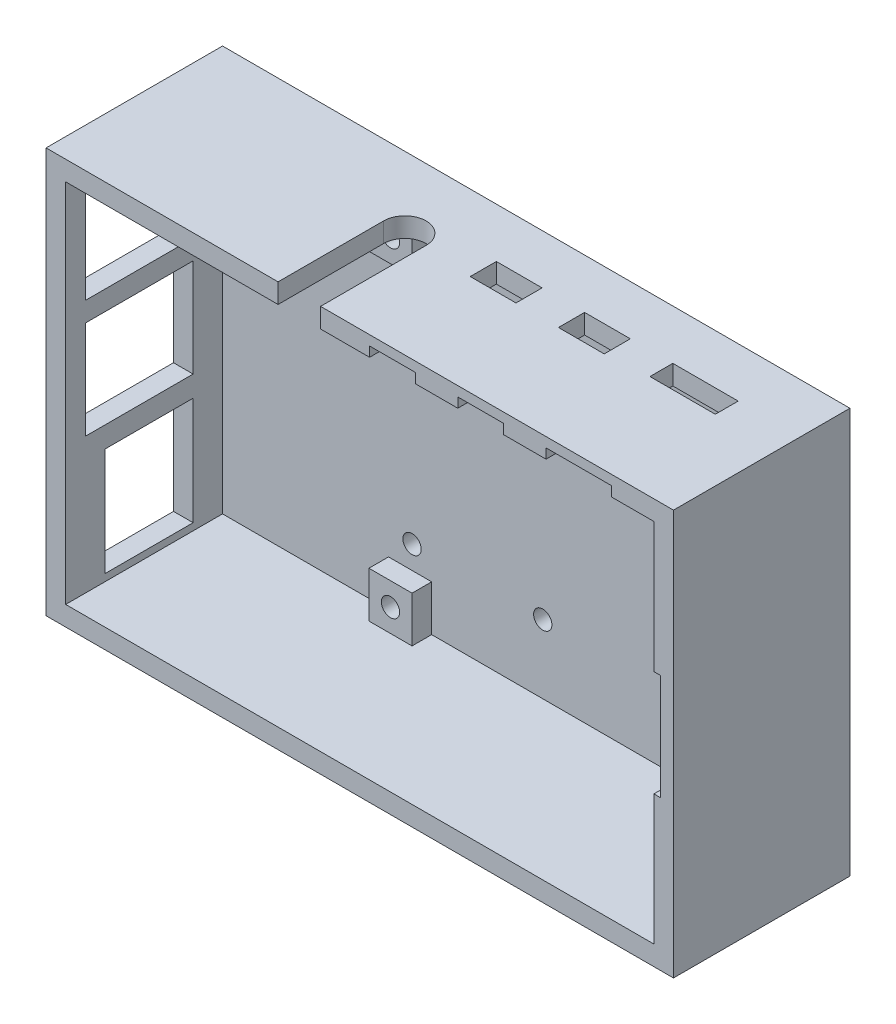
SolidWorks part; units mm, degrees
ref_plane "정면" through (0, 0, 0) normal (0, 0, 1) x (1, 0, 0)
ref_plane "윗면" through (0, 0, 0) normal (0, 1, 0) x (1, 0, 0)
ref_plane "우측면" through (0, 0, 0) normal (1, 0, 0) x (0, 0, -1)
sketch "스케치1" plane through (0, 0, 0) normal (0, 0, 1) x (1, 0, 0)
  line L0 (-16.3, 24.5) -> (41.7, 24.5) construction
  line L1 (-45, 28) -> (45, 28)
  line L2 (-45, 28) -> (-45, -28)
  line L3 (-45, -28) -> (45, -28)
  line L4 (45, 28) -> (45, -28)
  line L5 (-45, 28) -> (45, -28) construction
  line L6 (-45, -28) -> (45, 28) construction
  line L7 (0, 0) -> (-45, 0) construction
  circle A0 centre (-16.3, 24.5) radius 1.4
  circle A4 centre (41.7, 24.5) radius 1.4
  circle A5 centre (41.7, -24.5) radius 1.4
  circle A6 centre (-16.3, -24.5) radius 1.4
  point P0 (0, 0)
  point P9 (-9.134, -16.0476)
  point P17 (-17.4513, 16.1217)
  point P18 (0, 0)
  point P19 (0, 0)
  point P20 (-45, 30.5647)
  point P21 (0, 0)
  dimension "D1" = 2.8
  dimension "D3" = 2.8
  dimension "D2" = 90
  dimension "D4" = 58
  dimension "D5" = 49
  dimension "D6" = 56
  dimension "D7" = 3.3
extrude "보스-돌출1" add sketch "스케치1" along normal blind 3
sketch "스케치2" plane through (0, 0, 3) normal (0, 0, 1) x (1, 0, 0)
  line L0 (45, -28) -> (45, 28) construction
  line L1 (-19.6, 28) -> (-13, 28)
  line L2 (-19.6, 28) -> (-19.6, 21)
  line L3 (-19.6, 21) -> (-13, 21)
  line L4 (-13, 28) -> (-13, 21)
  line L5 (-19.6, 28) -> (-13, 21) construction
  line L6 (-19.6, 21) -> (-13, 28) construction
  line L7 (38.4, 28) -> (45, 28)
  line L8 (38.4, 28) -> (38.4, 21)
  line L9 (38.4, 21) -> (45, 21)
  line L10 (45, 28) -> (45, 21)
  line L11 (38.4, 28) -> (45, 21) construction
  line L12 (38.4, 21) -> (45, 28) construction
  line L13 (-45, -28) -> (45, -28) construction
  line L14 (38.4, -28) -> (45, -28)
  line L15 (38.4, -28) -> (38.4, -21)
  line L16 (38.4, -21) -> (45, -21)
  line L17 (45, -28) -> (45, -21)
  line L18 (38.4, -28) -> (45, -21) construction
  line L19 (38.4, -21) -> (45, -28) construction
  line L20 (-19.6, -21) -> (-13, -21)
  line L21 (-19.6, -21) -> (-19.6, -28)
  line L22 (-19.6, -28) -> (-13, -28)
  line L23 (-13, -21) -> (-13, -28)
  line L24 (-19.6, -21) -> (-13, -28) construction
  line L25 (-19.6, -28) -> (-13, -21) construction
  line L26 (45, 28) -> (-45, 28) construction
  circle A5 centre (-16.3, 24.5) radius 1.4 construction
  circle A6 centre (41.7, 24.5) radius 1.4 construction
  circle A7 centre (41.7, -24.5) radius 1.4 construction
  circle A8 centre (-16.3, -24.5) radius 1.4 construction
  circle A9 centre (-16.3, 24.5) radius 1.4
  circle A10 centre (41.7, 24.5) radius 1.4
  circle A11 centre (41.7, -24.5) radius 1.4
  circle A12 centre (-16.3, -24.5) radius 1.4
  point P0 (-16.3, 24.5)
  point P6 (-16.3, -24.5)
  point P10 (41.7, 24.5)
  point P20 (41.7, -24.5)
  dimension "D1" = 6.6
  dimension "D2" = 6.6
extrude "보스-돌출2" add sketch "스케치2" along normal blind 3
sketch "스케치3" plane through (0, 0, 0) normal (0, 0, 1) x (1, 0, 0)
  line L15 (45, -21) -> (45, 21) construction
  line L16 (-48, 31) -> (48, 31)
  line L20 (-45, -28) -> (-19.6, -28) construction
  line L41 (-48, 31) -> (-48, -31)
  line L42 (-48, -31) -> (48, -31)
  line L43 (48, 31) -> (48, -31)
  line L44 (-48, 31) -> (48, -31) construction
  line L45 (-48, -31) -> (48, 31) construction
  line L46 (-13, -28) -> (38.4, -28) construction
  line L47 (38.4, 28) -> (-13, 28) construction
  line L48 (-45, 28) -> (-45, -28) construction
  line L50 (-45, 28) -> (45, 28)
  line L51 (-45, 28) -> (-45, -28)
  line L52 (-45, -28) -> (45, -28)
  line L53 (45, 28) -> (45, -28)
  line L54 (-45, 28) -> (45, -28) construction
  line L55 (-45, -28) -> (45, 28) construction
  point P9 (-32.3, -28)
  point P11 (0, 0)
  point P16 (45, 0)
  point P19 (0, 0)
  dimension "D1" = 3
  dimension "D2" = 3
  dimension "D3" = 3
  dimension "D4" = 3
extrude "보스-돌출3" add sketch "스케치3" along normal blind 27
sketch "스케치4" plane through (-48, 0, 0) normal (-1, 0, 0) x (0, 0, 1)
  line L1 (24, 10.7807) -> (7.5, 10.7807)
  line L2 (24, 10.7807) -> (24, 25.7807)
  line L3 (24, 25.7807) -> (7.5, 25.7807)
  line L4 (7.5, 10.7807) -> (7.5, 25.7807)
  line L6 (24, -7.2193) -> (7.5, -7.2193)
  line L7 (24, -7.2193) -> (24, 7.7807)
  line L8 (24, 7.7807) -> (7.5, 7.7807)
  line L9 (7.5, -7.2193) -> (7.5, 7.7807)
  line L10 (7.5, -10.4193) -> (21, -10.4193)
  line L11 (7.5, -10.4193) -> (7.5, -26.9193)
  line L12 (7.5, -26.9193) -> (21, -26.9193)
  line L13 (21, -10.4193) -> (21, -26.9193)
  line L14 (6, 28) -> (6, 21) construction
  dimension "D1" = 16.5
  dimension "D2" = 15
  dimension "D3" = 15
  dimension "D4" = 3
  dimension "D5" = 3.2
  dimension "D6" = 1.5
  dimension "D7" = 13.5
  dimension "D8" = 16.5
extrude "컷-돌출1" cut sketch "스케치4" against normal up to surface (3 mm away) up to face at (-45, 0, 15)
sketch "스케치5" plane through (0, 31, 0) normal (0, 1, 0) x (1, 0, 0)
  line L1 (38.5, -11.1) -> (28.5, -11.1)
  line L2 (38.5, -11.1) -> (38.5, -7.6)
  line L3 (38.5, -7.6) -> (28.5, -7.6)
  line L4 (28.5, -11.1) -> (28.5, -7.6)
  line L5 (45, -6) -> (38.4, -6) construction
  line L6 (45, -27) -> (45, -6) construction
  line L7 (-6, -10.85) -> (-6, -3) construction
  line L8 (22, -7.6) -> (15, -7.6)
  line L9 (22, -7.6) -> (22, -11.6)
  line L10 (22, -11.6) -> (15, -11.6)
  line L11 (15, -7.6) -> (15, -11.6)
  line L12 (8.5, -7.6) -> (1.5, -7.6)
  line L13 (8.5, -7.6) -> (8.5, -11.6)
  line L14 (8.5, -11.6) -> (1.5, -11.6)
  line L15 (1.5, -7.6) -> (1.5, -11.6)
  line L16 (38.4, -3) -> (-13, -3) construction
  line L17 (-9.25, -7.6) -> (1.5, -7.6) construction
  line L18 (-12.5, -10.85) -> (-12.5, -27)
  line L19 (48, -27) -> (-48, -27) construction
  line L20 (-12.5, -27) -> (-6, -27)
  line L21 (-6, -27) -> (-6, -10.85)
  arc A0 (-6, -10.85) -> (-12.5, -10.85) centre (-9.25, -10.85) ccw
  dimension "D11" = 6.5
  dimension "D1" = 5.1
  dimension "D2" = 3.5
  dimension "D3" = 10
  dimension "D4" = 6.5
  dimension "D5" = 6.5
  dimension "D6" = 6.5
  dimension "D7" = 7
  dimension "D8" = 7
  dimension "D9" = 4
  dimension "D10" = 4
  dimension "D12" = 7.5
extrude "컷-돌출2" cut sketch "스케치5" against normal up to next
sketch "스케치6" plane through (0, 0, 27) normal (0, 0, 1) x (1, 0, 0)
  line L0 (8.5, 28) -> (8.5, 31) construction
  line L1 (1.5, 28) -> (8.5, 28)
  line L2 (1.5, 28) -> (1.5, 29.5)
  line L3 (1.5, 29.5) -> (8.5, 29.5)
  line L4 (8.5, 28) -> (8.5, 29.5)
  line L5 (22, 28) -> (22, 31) construction
  line L6 (15, 28) -> (22, 28)
  line L7 (15, 28) -> (15, 29.5)
  line L8 (15, 29.5) -> (22, 29.5)
  line L9 (22, 28) -> (22, 29.5)
  line L10 (38.5, 28) -> (38.5, 31) construction
  line L11 (28.5, 28) -> (38.5, 28)
  line L12 (28.5, 28) -> (28.5, 29.5)
  line L13 (28.5, 29.5) -> (38.5, 29.5)
  line L14 (38.5, 28) -> (38.5, 29.5)
extrude "컷-돌출3" cut sketch "스케치6" against normal up to next
sketch "스케치7" plane through (0, 0, 0) normal (0, 0, 1) x (1, 0, 0)
  line L1 (46, 8.1) -> (44, 8.1)
  line L2 (46, 8.1) -> (46, -8.1)
  line L3 (46, -8.1) -> (44, -8.1)
  line L4 (44, 8.1) -> (44, -8.1)
  line L5 (0, 0) -> (44, 0) construction
  line L6 (45, -28) -> (45, 28) construction
  dimension "D1" = 16.2
  dimension "D2" = 2
  dimension "D3" = 1
extrude "컷-돌출6" cut sketch "스케치7" against normal blind 5 and the other way through all
sketch "스케치8" plane through (0, 0, 0) normal (0, 0, -1) x (-1, 0, 0)
  line L0 (0, 0) -> (50, 0) construction
  line L1 (-4, 17.5) -> (16, 17.5) construction
  circle A0 centre (-4, 17.5) radius 1.4
  circle A1 centre (16, 17.5) radius 1.4
  circle A4 centre (-4, -17.5) radius 1.4
  circle A5 centre (16, -17.5) radius 1.4
  dimension "D1" = 2.8
  dimension "D2" = 20
  dimension "D3" = 50
  dimension "D4" = 2.8
  dimension "D5" = 35
  dimension "D6" = 4
extrude "컷-돌출7" cut sketch "스케치8" against normal blind 5
